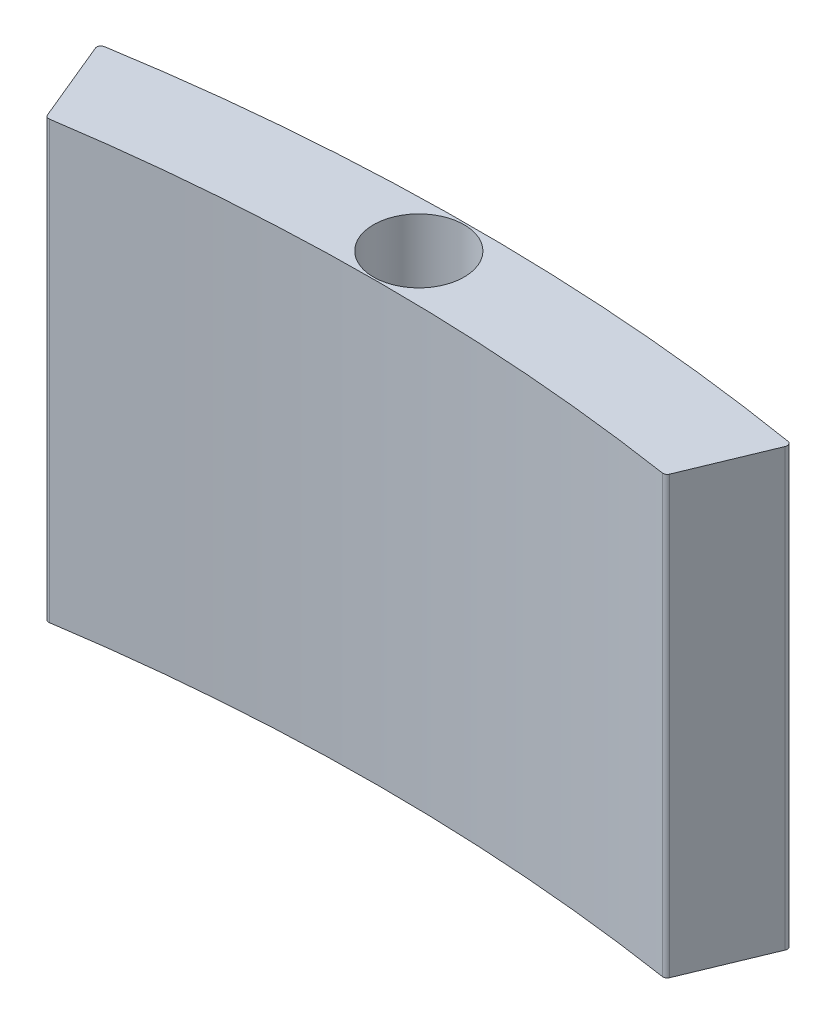
SolidWorks part; units mm, degrees
ref_plane "Front Plane" through (0, 0, 0) normal (0, 0, 1) x (1, 0, 0)
ref_plane "Top Plane" through (0, 0, 0) normal (0, 1, 0) x (1, 0, 0)
ref_plane "Right Plane" through (0, 0, 0) normal (1, 0, 0) x (0, 0, -1)
sketch "Sketch1" plane through (0, 0, 0) normal (0, 1, 0) x (1, 0, 0)
  line L0 (18.2696, -2.357) -> (20.2109, 2.3299)
  line L1 (-19.3347, 2.3299) -> (-17.3934, -2.357)
  line L2 (0, 0) -> (0, 11.2373) construction
  arc A0 (18.0042, -2.5064) -> (18.2696, -2.357) centre (18.0417, -2.2626) ccw
  arc A1 (20.2109, 2.3299) -> (20.0229, 2.6677) centre (19.9831, 2.4243) ccw
  arc A2 (20.0229, 2.6677) -> (-19.1467, 2.6677) centre (0.4381, -116.8512) ccw
  arc A3 (-19.1467, 2.6677) -> (-19.3347, 2.3299) centre (-19.1068, 2.4243) ccw
  arc A4 (-17.3934, -2.357) -> (-17.128, -2.5064) centre (-17.1655, -2.2626) ccw
  arc A5 (18.0042, -2.5064) -> (-17.128, -2.5064) centre (0.4381, -116.8512) ccw
  circle A6 centre (0, 1.5367) radius 2.6
  point P19 (0, 0)
  point P20 (0, 1.4252)
  point P21 (0, 1.5367)
  dimension "D1" = 5.2
extrude "Boss-Extrude1" add sketch "Sketch1" along normal mid plane 25
